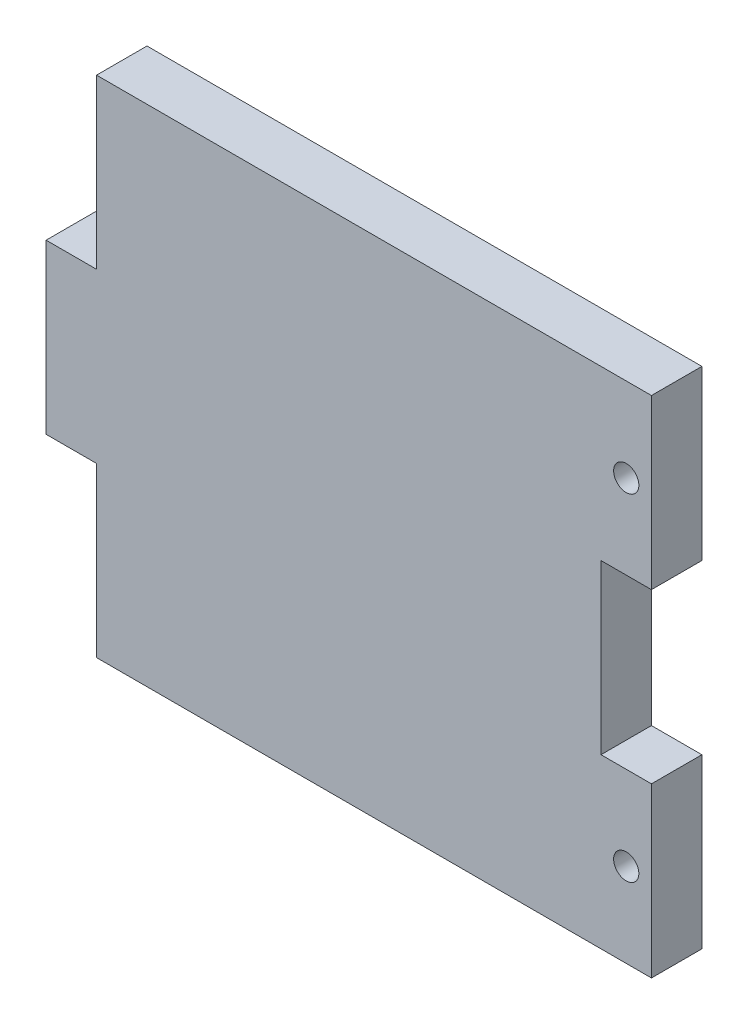
SolidWorks part; units mm, degrees
ref_plane "Plan de face" through (0, 0, 0) normal (0, 0, 1) x (1, 0, 0)
ref_plane "Plan de dessus" through (0, 0, 0) normal (0, 1, 0) x (1, 0, 0)
ref_plane "Plan de droite" through (0, 0, 0) normal (1, 0, 0) x (0, 0, -1)
sketch "Esquisse1" plane through (0, 0, 0) normal (0, 0, 1) x (1, 0, 0)
  line L0 (0, 0) -> (-66, 60) construction
  line L1 (0, 0) -> (-66, 0)
  line L2 (0, 0) -> (0, 20)
  line L3 (0, 60) -> (-66, 60)
  line L4 (-66, 0) -> (-66, 20)
  line L5 (0, 40) -> (-6, 40)
  line L6 (-66, 0) -> (0, 60) construction
  line L7 (0, 20) -> (-6, 20)
  line L8 (-6, 40) -> (-6, 20)
  line L9 (0, 40) -> (0, 60)
  line L10 (-66, 40) -> (-72, 40)
  line L11 (-33, 30) -> (-72, 30) construction
  line L12 (-66, 20) -> (-72, 20)
  line L13 (-72, 40) -> (-72, 20)
  line L14 (-66, 40) -> (-66, 60)
  line L15 (-33, 30) -> (-6, 30) construction
  dimension "D1" = 60
  dimension "D2" = 66
  dimension "D3" = 6
  dimension "D4" = 20
  dimension "D5" = 6
  dimension "D6" = 20
extrude "Boss.-Extru.1" add sketch "Esquisse1" along normal blind 6
sketch "Esquisse2" plane through (0, 0, 0) normal (0, 0, -1) x (-1, 0, 0)
  line L0 (72, 30) -> (-12.9835, 30) construction
  line L1 (0, 0) -> (0, 20) construction
  line L2 (72, 40) -> (72, 20) construction
  line L3 (3, 60) -> (3, 20) construction
  line L6 (0, 60) -> (66, 60) construction
  line L7 (3, 20) -> (3, 0) construction
  line L8 (66, 0) -> (0, 0) construction
  circle A0 centre (3, 50) radius 1.5
  circle A1 centre (3, 10) radius 1.5
  dimension "D1" = 10
  dimension "D3" = 3
  dimension "D2" = 3
extrude "Enlèv. mat.-Extru.1" cut sketch "Esquisse2" against normal through all
